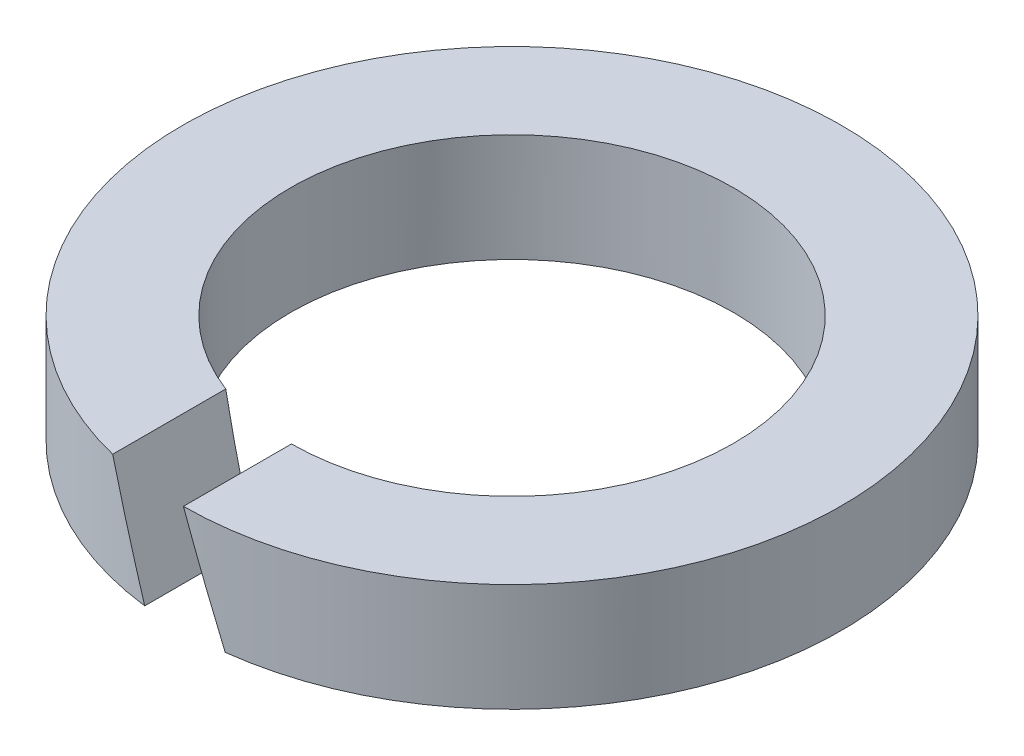
SolidWorks part; units mm, degrees
ref_plane "Спереди" through (0, 0, 0) normal (0, 0, 1) x (1, 0, 0)
ref_plane "Сверху" through (0, 0, 0) normal (0, 1, 0) x (1, 0, 0)
ref_plane "Справа" through (0, 0, 0) normal (1, 0, 0) x (0, 0, -1)
sketch "Ske" plane through (0, 0, 0) normal (0, 0, 1) x (1, 0, 0)
  line L0 (0, 15.7597) -> (0, -13.7032) construction
  line L1 (-2.05, 0) -> (-3.05, 0)
  line L2 (-2.05, 0) -> (-2.05, 1)
  line L3 (-2.05, 1) -> (-3.05, 1)
  line L4 (-3.05, 0) -> (-3.05, 1)
  dimension "S" = 1
  dimension "H" = 1
  dimension "Insid_Dia" = 4.1
revolve "Base" add sketch "Ske" angle 360 about L0
sketch "Ske4" plane through (0, 0, 0) normal (0, 0, 1) x (1, 0, 0)
  line L0 (0, 0) -> (-0.6869, 1.8873) construction
  line L1 (-2.05, 0) -> (2.05, 0) construction
  line L2 (2.05, 1) -> (-2.05, 1) construction
  line L3 (-0.3725, 0) -> (0.3725, 0)
  line L4 (0.0085, 1) -> (-0.7364, 1)
  line L5 (0.0085, 1) -> (0.3725, 0)
  line L6 (-0.7364, 1) -> (-0.3725, 0)
  dimension "D1" = 110
  dimension "D2" = 0.7
extrude "Cut" cut sketch "Ske4" along normal up to next
equation "\"D2@Ske4\"=0.7*\"H@Ske\""
